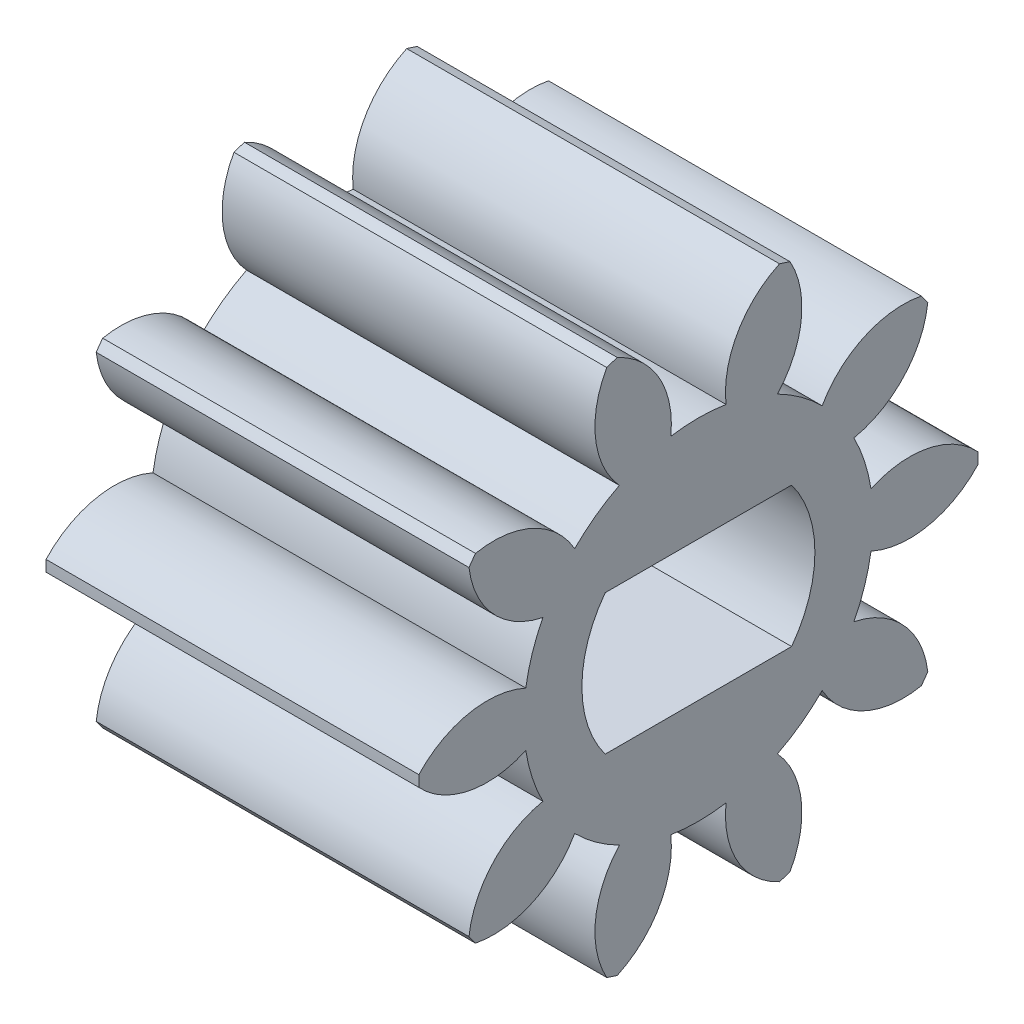
SolidWorks part; units mm, degrees
ref_plane "Plane1" through (0, 0, 0) normal (0, 0, 1) x (1, 0, 0)
ref_plane "Plane2" through (0, 0, 0) normal (0, 1, 0) x (1, 0, 0)
ref_plane "Plane3" through (0, 0, 0) normal (1, 0, 0) x (0, 0, -1)
sketch "HoldingSke" plane through (0, 0, 0) normal (0, 1, 0) x (1, 0, 0)
  line L0 (0, 0) -> (0.9848, -0.1736)
  line L1 (-15, 0) -> (100, 0) construction
  line L2 (0, 0) -> (-2.1039, 2.3779)
  line L3 (0, 0) -> (-11.863, 4.5341)
  line L4 (0, 0) -> (8.5048, 1.4996)
  line L5 (0, 0) -> (-46.8476, -17.4728)
  line L6 (0, 0) -> (-6.6317, -4.4744)
  line L7 (-2.1039, 2.3779) -> (8.6586, 51.2059)
  line L8 (-76.2, 54.61) -> (-75.3, 54.61)
  line L9 (-71.009, 38.7566) -> (-53.1078, 45.2721)
  line L10 (-76.2, 71.12) -> (104.1128, 71.12)
  line L11 (0, 0) -> (-8, 0)
  line L12 (-76.2, 101.6) -> (-76.162, 101.6)
  line L13 (24.9733, 27.94) -> (52.9518, 28.4284)
  line L14 (24.9733, 27.94) -> (24.9743, 27.94)
  line L15 (24.9733, 27.94) -> (100.4006, 29.5858)
  line L16 (-63.627, -1) -> (-12.827, -1)
  circle A0 centre (0, 0) radius 2.5
  circle A1 centre (0, 0) radius 3.749
  circle A2 centre (0, 0) radius 37.5
  circle A3 centre (0, 0) radius 2.5
  dimension "MHD" = 7.498
  dimension "Hub_dia" = 75
  dimension "Bore" = 5
  dimension "MBD" = 5
  dimension "Num_teeth" = 10
  dimension "Pitch" = 1
  dimension "Overall_len" = 50
  dimension "Show_teeth" = 10
  dimension "Thickness" = 8
  dimension "OAL" = 50.0001
  dimension "T_dim" = 0.9
  dimension "Ap" = 20
  dimension "H" = 19.05
  dimension "Pitch_radius" = 180.3128
  dimension "Width" = 8
  dimension "Backlash" = 0.038
  dimension "Addendum_fac" = 1
  dimension "Dedendum_fac" = 1.25
  dimension "Clearance_fac" = 0.25
  dimension "Dedendum_add" = 0.001
  dimension "Module" = 1
sketch "BasProSke" plane through (0, 0, 0) normal (0, 1, 0) x (1, 0, 0)
  line L0 (-10, 0) -> (60, 0) construction
  line L1 (0, 0) -> (0, 6)
  line L2 (0, 0) -> (8, 0)
  line L3 (8, 0) -> (8, 6)
  line L4 (8, 6) -> (0, 6)
  dimension "Thickness" = 8
  dimension "Diameter" = 12
revolve "Base-Revolve" add sketch "BasProSke" angle 360 about L0
sketch "TooCutSke" plane through (0, 0, 0) normal (1, 0, 0) x (0, 0, -1)
  line L1 (0, 0) -> (0, 107) construction
  line L2 (0, 0) -> (-0.8485, 4.9275) construction
  line L3 (0, 0) -> (-3.0584, 9.4126) construction
  line L4 (-0.8485, 4.9275) -> (-1.5292, 4.7063) construction
  arc A0 (0.5928, 3.7018) -> (-0.5928, 3.7018) centre (0, 0) ccw
  arc A1 (1.7758, 5.7578) -> (-1.7758, 5.7578) centre (0, 0) ccw
  circle A2 centre (0, 0) radius 5 construction
  circle A3 centre (0, 0) radius 4.6985 construction
  arc A4 (-0.5928, 3.7018) -> (-1.7758, 5.7578) centre (-2.5801, 3.9267) ccw
  arc A5 (1.7758, 5.7578) -> (0.5928, 3.7018) centre (2.5801, 3.9267) ccw
  dimension "Root_dia" = 7.498
  dimension "Overcut_dia" = 12.0508
  dimension "Pitch_dia" = 10
  dimension "Base_dia" = 9.3969
  dimension "Flank_rad" = 2
  dimension "Half_ang" = 18
  dimension "Half_CT" = 0.7157
extrude "ToothCut" cut sketch "TooCutSke" along normal through all
fillet "Breaks" [suppressed] radius 0.02
fillet "RootFillets" [suppressed] radius 0.251
pattern_circular "TeethCuts" count 10 every 36 about axis through (-10, 0, 0) along (1, 0, 0) of "ToothCut", "RootFillets", "Breaks"
sketch "HubNeaOneSke" plane through (0, 0, 0) normal (-1, 0, 0) x (0, 0, 1)
  circle A0 centre (0, 0) radius 3.749
  dimension "Diameter" = 7.498
extrude "HubNearOne" [suppressed] add sketch "HubNeaOneSke" along normal blind 42.0001
sketch "HubNeaBotSke" plane through (0, 0, 0) normal (-1, 0, 0) x (0, 0, 1)
  circle A0 centre (0, 0) radius 3.749
  dimension "Diameter" = 7.498
extrude "HubNearBoth" [suppressed] add sketch "HubNeaBotSke" along normal blind 21
ref_plane "FarPln" through (8, 0, 0) normal (1, 0, 0) x (0, 0, -1)
sketch "HubFarSke" plane through (8, 0, 0) normal (1, 0, 0) x (0, 0, -1)
  circle A0 centre (0, 0) radius 3.749
  dimension "Diameter" = 7.498
extrude "HubFar" [suppressed] add sketch "HubFarSke" along normal blind 21
sketch "BorSke" plane through (0, 0, 0) normal (1, 0, 0) x (0, 0, -1)
  circle A0 centre (0, 0) radius 2.5
  dimension "Diameter" = 5
extrude "Bore" cut sketch "BorSke" along normal mid plane 100.0001
sketch "KeySke" plane through (0, 0, 0) normal (1, 0, 0) x (0, 0, -1)
  line L0 (-1, 0) -> (-1, 3.4)
  line L1 (-1, 3.4) -> (1, 3.4)
  line L2 (1, 3.4) -> (1, 0)
  line L3 (0, 0) -> (0, 34) construction
  line L4 (-1, 0) -> (1, 0)
  dimension "Offset" = 3.4
  dimension "Width" = 2
extrude "Keyway" [suppressed] cut sketch "KeySke" along normal mid plane 100.0001
pattern_circular "Keyway2" [suppressed] count 2 every 90 about axis through (-10, 0, 0) along (1, 0, 0)
sketch "Esboço1" plane through (8, 0, 0) normal (1, 0, 0) x (0, 0, -1)
  line L0 (-2.5, 0) -> (2.5, 0)
  line L1 (-2.5, -1.5) -> (2.5, -1.5)
  line L2 (-2.5, 1.5) -> (2.5, 1.5)
  circle A0 centre (0, 0) radius 2.5 construction
  circle A1 centre (0, 0) radius 2.5
  circle M2 centre (0, 0) radius 2.5
  dimension "D1" = 1.5
  dimension "D2" = 1.5
extrude "Ressalto-extrusão3" add sketch "Esboço1" against normal up to surface (8 mm away) contours L2 M2 | L1 M2 up to face at (0, 0, -2.5)
equation "' \"Module@HoldingSke\" = 6.35"
equation "' \"Num_teeth@HoldingSke\" = 12"
equation "' \"Ap@HoldingSke\" =  20"
equation "' \"Ap@HoldingSke\" = 20"
equation "' \"Width@HoldingSke\" = 0.5 * 25.4"
equation "' \"Hub_dia@HoldingSke\"= 1 * 25.4"
equation "' \"Hub_dia@HoldingSke\" = 1 * 25.4"
equation "' \"Overall_len@HoldingSke\" = 1.0 * 25.4"
equation "' \"Bore@HoldingSke\" = 0.75 * 25.4"
equation "' \"T_dim@HoldingSke\" = 0.1 * 25.4"
equation "' \"Width@KeySke\" = 0.25 * 25.4"
equation "' \"Show_teeth@HoldingSke\" = 13"
equation "' \"Backlash@HoldingSke\" = 0.009 * 25.4"
equation "' \"Addendum_fac@HoldingSke\" = 1.0"
equation "' \"Dedendum_fac@HoldingSke\" = 1.25"
equation "' \"Dedendum_add@HoldingSke\" = 0.00005 * 25.4"
equation "' \"Clearance_fac@HoldingSke\" = 0.25"
equation "\"Pitch@HoldingSke\" = 1 / \"Module@HoldingSke\""
equation "\"Overcut_dia@TooCutSke\" = (\"Num_teeth@HoldingSke\" + 2 * \"Addendum_fac@HoldingSke\") / \"Pitch@HoldingSke\" + 0.002 * 25.4"
equation "\"Pitch_dia@TooCutSke\" = \"Num_teeth@HoldingSke\" / \"Pitch@HoldingSke\""
equation "\"Base_dia@TooCutSke\" = \"Num_teeth@HoldingSke\" / \"Pitch@HoldingSke\" * cos((\"Ap@HoldingSke\"  * 3.14159265 / 180))"
equation "\"Root_dia@TooCutSke\" = (\"Num_teeth@HoldingSke\" + 2) / \"Pitch@HoldingSke\" - 2 * (\"Addendum_fac@HoldingSke\" + \"Dedendum_fac@HoldingSke\") / \"Pitch@HoldingSke\" - \"Dedendum_add@HoldingSke\" * 2"
equation "\"Half_ang@TooCutSke\" = 180 / \"Num_teeth@HoldingSke\""
equation "\"Half_CT@TooCutSke\" = \"Num_teeth@HoldingSke\" / \"Pitch@HoldingSke\" * sin((3.14159265 / 2 / \"Num_teeth@HoldingSke\")) / 2 - 7 * \"Backlash@HoldingSke\" / 4"
equation "\"Flank_rad@TooCutSke\" = \"Num_teeth@HoldingSke\" / \"Pitch@HoldingSke\" / 5"
equation "\"Radius@RootFillets\" = \"Clearance_fac@HoldingSke\" / \"Pitch@HoldingSke\" + \"Dedendum_add@HoldingSke\""
equation "\"Break_rad@Breaks\" = 0.02 / \"Pitch@HoldingSke\""
equation "\"Thickness@HoldingSke\" = \"Width@HoldingSke\""
equation "\"OAL@HoldingSke\" = \"Thickness@HoldingSke\""
equation "\"MHD@HoldingSke\" = (\"Num_teeth@HoldingSke\" + 2) / \"Pitch@HoldingSke\" - 2 * (\"Addendum_fac@HoldingSke\" + \"Dedendum_fac@HoldingSke\")  / \"Pitch@HoldingSke\" - \"Dedendum_add@HoldingSke\" * 2"
equation "\"MBD@HoldingSke\" = (\"Num_teeth@HoldingSke\" + 2) / \"Pitch@HoldingSke\" - 2 * (\"Addendum_fac@HoldingSke\" + \"Dedendum_fac@HoldingSke\")  / \"Pitch@HoldingSke\" - \"Dedendum_add@HoldingSke\" * 2 - 0.002 * 25.4"
equation "\"MHD@HoldingSke\" = ((sgn( \"MHD@HoldingSke\" - \"Hub_dia@HoldingSke\" )-1)*( \"MHD@HoldingSke\" - \"Hub_dia@HoldingSke\" ))/-2+ \"Hub_dia@HoldingSke\""
equation "\"MBD@HoldingSke\" = ((sgn( \"MBD@HoldingSke\" - \"Bore@HoldingSke\" )-1)*( \"MBD@HoldingSke\" - \"Bore@HoldingSke\" ))/-2+ \"Bore@HoldingSke\""
equation "\"OAL@HoldingSke\" = ((sgn( \"OAL@HoldingSke\" - \"Overall_len@HoldingSke\" )+1)*( \"OAL@HoldingSke\" - \"Overall_len@HoldingSke\" ))/2 + \"Overall_len@HoldingSke\" + 0.000002 * 25.4"
equation "\"Num_teeth@TeethCuts\" = int( \"Show_teeth@HoldingSke\" ) + 1"
equation "\"Num_teeth@TeethCuts\" = ((sgn( \"Num_teeth@TeethCuts\" - \"Num_teeth@HoldingSke\" )-1)*( \"Num_teeth@TeethCuts\" - \"Num_teeth@HoldingSke\" ))/-2+ \"Num_teeth@HoldingSke\""
equation "\"Num_teeth@TeethCuts\" = ((sgn( \"Num_teeth@TeethCuts\" - 2.0)+1)*( \"Num_teeth@TeethCuts\" - 2.0))/2 +2.0"
equation "\"Angle@TeethCuts\" = 360.0 / \"Num_teeth@HoldingSke\""
equation "\"Diameter@BasProSke\" = (\"Num_teeth@HoldingSke\" + 2 * \"Addendum_fac@HoldingSke\") / \"Pitch@HoldingSke\""
equation "\"Thickness@BasProSke\"  = \"Thickness@HoldingSke\""
equation "' \"Fillet_rad@BasProSke\" =  \"Thickness@HoldingSke\" * 0.05"
equation "' \"Fillet_rad@BasProSke\" = \"Thickness@HoldingSke\" * 0.05"
equation "\"MHD@HoldingSke\" = ((sgn( \"MHD@HoldingSke\" - \"Root_dia@TooCutSke\" )-1)*( \"MHD@HoldingSke\" - \"Root_dia@TooCutSke\" ))/-2+ \"Root_dia@TooCutSke\""
equation "\"Diameter@HubNeaOneSke\" = \"MHD@HoldingSke\""
equation "\"Length@HubNearOne\" = \"OAL@HoldingSke\" - \"Thickness@BasProSke\""
equation "\"Diameter@HubNeaBotSke\" = \"MHD@HoldingSke\""
equation "\"Length@HubNearBoth\" = ( \"OAL@HoldingSke\" - \"Thickness@BasProSke\" ) / 2.0"
equation "\"Thickness@FarPln\" = \"Thickness@BasProSke\""
equation "\"Diameter@HubFarSke\" = \"MHD@HoldingSke\""
equation "\"Length@HubFar\" = ( \"OAL@HoldingSke\" - \"Thickness@BasProSke\" ) / 2.0"
equation "\"Diameter@BorSke\" = \"MBD@HoldingSke\""
equation "\"D1@Bore\" = \"OAL@HoldingSke\" * 2.0"
equation "\"D1@Keyway\" = \"OAL@HoldingSke\" * 2.0"
equation "\"Offset@KeySke\" = \"T_dim@HoldingSke\" + \"MBD@HoldingSke\" / 2.0"
